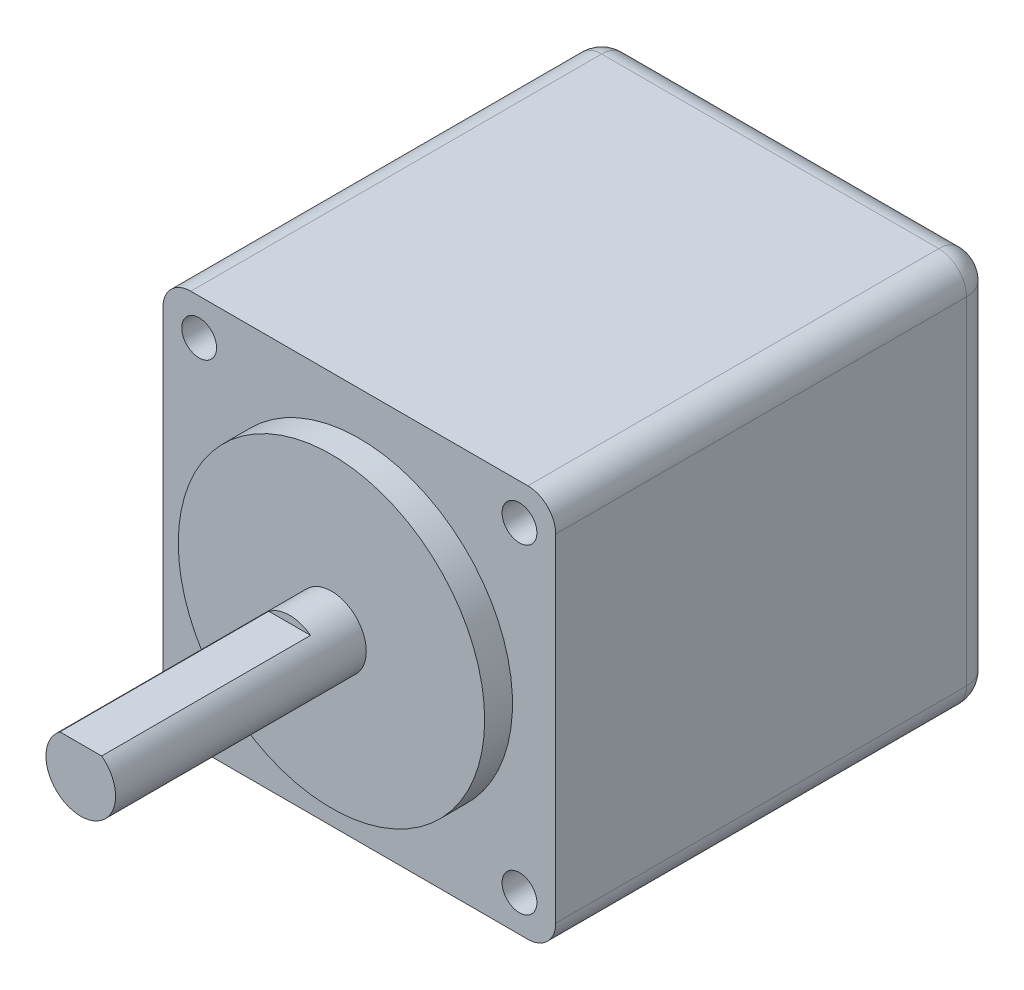
SolidWorks part; units mm, degrees
ref_plane "Front Plane" through (0, 0, 0) normal (0, 0, 1) x (1, 0, 0)
ref_plane "Top Plane" through (0, 0, 0) normal (0, 1, 0) x (1, 0, 0)
ref_plane "Right Plane" through (0, 0, 0) normal (1, 0, 0) x (0, 0, -1)
sketch "Sketch1" plane through (0, 0, 0) normal (0, 0, 1) x (1, 0, 0)
  line L1 (-14.1, -14.1) -> (14.1, -14.1)
  line L2 (-14.1, -14.1) -> (-14.1, 14.1)
  line L3 (-14.1, 14.1) -> (14.1, 14.1)
  line L4 (14.1, -14.1) -> (14.1, 14.1)
  line L5 (-14.1, -14.1) -> (14.1, 14.1) construction
  line L6 (-14.1, 14.1) -> (14.1, -14.1) construction
  point P0 (0, 0)
  dimension "D1" = 28.2
  dimension "D2" = 28.2
extrude "Boss-Extrude1" add sketch "Sketch1" along normal blind 31.5
sketch "Sketch2" plane through (0, 0, 31.5) normal (0, 0, 1) x (1, 0, 0)
  circle A0 centre (0, 0) radius 11
  dimension "D1" = 22
extrude "Boss-Extrude2" add sketch "Sketch2" along normal blind 2
sketch "Sketch3" plane through (0, 0, 33.5) normal (0, 0, 1) x (1, 0, 0)
  circle A0 centre (0, 0) radius 2.5
  dimension "D1" = 5
extrude "Boss-Extrude3" add sketch "Sketch3" along normal blind 18
sketch "Sketch4" plane through (0, 0, 0) normal (1, 0, 0) x (0, 0, -1)
  line L1 (-51.5, 2.5) -> (-36.5, 2.5)
  line L2 (-51.5, 2.5) -> (-51.5, 2)
  line L3 (-51.5, 2) -> (-36.5, 2)
  line L4 (-36.5, 2.5) -> (-36.5, 2)
  dimension "D1" = 15
  dimension "D2" = 0.5
extrude "Cut-Extrude1" cut sketch "Sketch4" against normal mid plane 10
sketch "Sketch5" plane through (0, 0, 31.5) normal (0, 0, 1) x (1, 0, 0)
  line L1 (-11.5, -11.5) -> (11.5, -11.5) construction
  line L2 (-11.5, -11.5) -> (-11.5, 11.5) construction
  line L3 (-11.5, 11.5) -> (11.5, 11.5) construction
  line L4 (11.5, -11.5) -> (11.5, 11.5) construction
  line L5 (-11.5, -11.5) -> (11.5, 11.5) construction
  line L6 (-11.5, 11.5) -> (11.5, -11.5) construction
  circle A0 centre (-11.5, 11.5) radius 1.25
  circle A1 centre (11.5, 11.5) radius 1.25
  circle A2 centre (11.5, -11.5) radius 1.25
  circle A3 centre (-11.5, -11.5) radius 1.25
  point P0 (0, 0)
  dimension "D3" = 2.5
  dimension "D1" = 23
  dimension "D2" = 23
  dimension "D4" = 4
extrude "Cut-Extrude2" cut sketch "Sketch5" against normal blind 2.5
fillet "Fillet1" radius 2 8 edges at (0, 14.1, 0) (-14.1, 0, 0) (0, -14.1, 0) (14.1, 0, 0) (-14.1, -14.1, 15.75) (14.1, -14.1, 15.75) (-14.1, 14.1, 15.75) (14.1, 14.1, 15.75)
